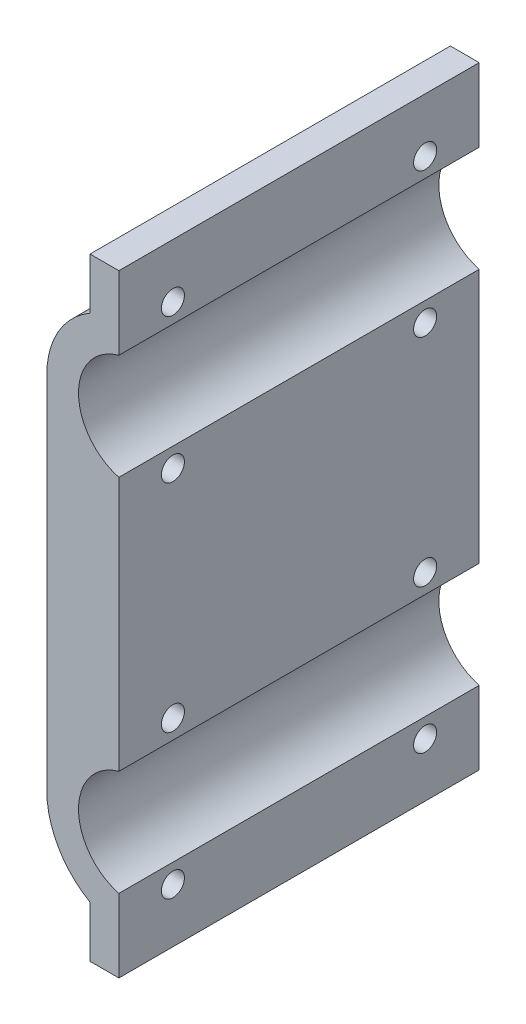
SolidWorks part; units mm, degrees
ref_plane "Plano frontal" through (0, 0, 0) normal (0, 0, 1) x (1, 0, 0)
ref_plane "Plano superior" through (0, 0, 0) normal (0, 1, 0) x (1, 0, 0)
ref_plane "Plano direito" through (0, 0, 0) normal (1, 0, 0) x (0, 0, -1)
sketch "Esboço1" plane through (0, 0, 0) normal (0, 0, 1) x (1, 0, 0)
  line L0 (0, 17.6679) -> (0, -17.6679) construction
  line L1 (0, 17.6679) -> (0, -17.6679)
  line L2 (-10, 25) -> (-10, -25)
  line L3 (0, -32.3321) -> (0, -42.5)
  line L4 (0, -42.5) -> (-4, -42.5)
  line L5 (-4, -42.5) -> (-4, -35.3923)
  line L6 (0, 32.3321) -> (0, 42.5)
  line L7 (0, 42.5) -> (-4, 42.5)
  line L8 (-4, 42.5) -> (-4, 35.3923)
  arc A0 (0, 32.3321) -> (0, 17.6679) centre (2, 25) ccw
  arc A1 (0, -17.6679) -> (0, -32.3321) centre (2, -25) ccw
  arc A2 (-4, 35.3923) -> (-10, 25) centre (2, 25) ccw
  arc A3 (-10, -25) -> (-4, -35.3923) centre (2, -25) ccw
  point P0 (0, 42.5)
  point P1 (2.9032, -24.6696)
  point P5 (0, 0)
  point P12 (0, 25.2871)
  point P15 (0, 0)
  dimension "D1" = 15.2
  dimension "D2" = 12
  dimension "D3" = 50
  dimension "D4" = 85
  dimension "D5" = 4
  dimension "D6" = 2
extrude "Ressalto-extrusão1" add sketch "Esboço1" along normal blind 50
sketch "Esboço2" plane through (0, 0, 0) normal (1, 0, 0) x (0, 0, -1)
  line L0 (-50, 25) -> (0, 25) construction
  line L1 (-50, -25) -> (0, -25) construction
  line L2 (-50, -17.6679) -> (-50, -32.3321) construction
  line L3 (0, -32.3321) -> (0, -17.6679) construction
  line L4 (-25, 42.5) -> (-25, -42.5) construction
  line L5 (-50, 42.5) -> (0, 42.5) construction
  line L6 (-50, -42.5) -> (0, -42.5) construction
  circle A0 centre (-42.5, 35) radius 1.6
  circle A1 centre (-7.5, 35) radius 1.6
  circle A2 centre (-7.5, -35) radius 1.6
  circle A3 centre (-42.5, -35) radius 1.6
  circle A4 centre (-42.5, -15) radius 1.6
  circle A5 centre (-42.5, 15) radius 1.6
  circle A6 centre (-7.5, 15) radius 1.6
  circle A7 centre (-7.5, -15) radius 1.6
  dimension "D4" = 3.2
  dimension "D1" = 20
  dimension "D2" = 20
  dimension "D3" = 35
extrude "Corte-extrusão1" cut sketch "Esboço2" against normal through all
sketch "Esboço3" plane through (-10, 0, 0) normal (-1, 0, 0) x (0, 0, 1)
  line L0 (0, 25) -> (0, -25) construction
  line L1 (10.25, 36.5877) -> (7.5, 38.1754)
  line L2 (7.5, 38.1754) -> (4.75, 36.5877)
  line L3 (4.75, 36.5877) -> (4.75, 33.4123)
  line L4 (4.75, 33.4123) -> (7.5, 31.8246)
  line L5 (7.5, 31.8246) -> (10.25, 33.4123)
  line L6 (10.25, 33.4123) -> (10.25, 36.5877)
  line L7 (45.25, 36.5877) -> (42.5, 38.1754)
  line L8 (42.5, 38.1754) -> (39.75, 36.5877)
  line L9 (39.75, 36.5877) -> (39.75, 33.4123)
  line L10 (39.75, 33.4123) -> (42.5, 31.8246)
  line L11 (42.5, 31.8246) -> (45.25, 33.4123)
  line L12 (45.25, 33.4123) -> (45.25, 36.5877)
  line L13 (45.25, 16.5877) -> (42.5, 18.1754)
  line L14 (42.5, 18.1754) -> (39.75, 16.5877)
  line L15 (39.75, 16.5877) -> (39.75, 13.4123)
  line L16 (39.75, 13.4123) -> (42.5, 11.8246)
  line L17 (42.5, 11.8246) -> (45.25, 13.4123)
  line L18 (45.25, 13.4123) -> (45.25, 16.5877)
  line L19 (10.25, 16.5877) -> (7.5, 18.1754)
  line L20 (7.5, 18.1754) -> (4.75, 16.5877)
  line L21 (4.75, 16.5877) -> (4.75, 13.4123)
  line L22 (4.75, 13.4123) -> (7.5, 11.8246)
  line L23 (7.5, 11.8246) -> (10.25, 13.4123)
  line L24 (10.25, 13.4123) -> (10.25, 16.5877)
  line L25 (10.25, -13.4123) -> (7.5, -11.8246)
  line L26 (7.5, -11.8246) -> (4.75, -13.4123)
  line L27 (4.75, -13.4123) -> (4.75, -16.5877)
  line L28 (4.75, -16.5877) -> (7.5, -18.1754)
  line L29 (7.5, -18.1754) -> (10.25, -16.5877)
  line L30 (10.25, -16.5877) -> (10.25, -13.4123)
  line L31 (10.25, -33.4123) -> (7.5, -31.8246)
  line L32 (7.5, -31.8246) -> (4.75, -33.4123)
  line L33 (4.75, -33.4123) -> (4.75, -36.5877)
  line L34 (4.75, -36.5877) -> (7.5, -38.1754)
  line L35 (7.5, -38.1754) -> (10.25, -36.5877)
  line L36 (10.25, -36.5877) -> (10.25, -33.4123)
  line L37 (45.25, -33.4123) -> (42.5, -31.8246)
  line L38 (42.5, -31.8246) -> (39.75, -33.4123)
  line L39 (39.75, -33.4123) -> (39.75, -36.5877)
  line L40 (39.75, -36.5877) -> (42.5, -38.1754)
  line L41 (42.5, -38.1754) -> (45.25, -36.5877)
  line L42 (45.25, -36.5877) -> (45.25, -33.4123)
  line L43 (45.25, -13.4123) -> (42.5, -11.8246)
  line L44 (42.5, -11.8246) -> (39.75, -13.4123)
  line L45 (39.75, -13.4123) -> (39.75, -16.5877)
  line L46 (39.75, -16.5877) -> (42.5, -18.1754)
  line L47 (42.5, -18.1754) -> (45.25, -16.5877)
  line L48 (45.25, -16.5877) -> (45.25, -13.4123)
  circle A0 centre (7.5, 35) radius 2.75 construction
  circle A1 centre (42.5, 35) radius 2.75 construction
  circle A2 centre (42.5, 15) radius 2.75 construction
  circle A3 centre (7.5, 15) radius 2.75 construction
  circle A4 centre (7.5, -15) radius 2.75 construction
  circle A5 centre (7.5, -35) radius 2.75 construction
  circle A6 centre (42.5, -35) radius 2.75 construction
  circle A7 centre (42.5, -15) radius 2.75 construction
  dimension "D1" = 5.5
extrude "Corte-extrusão2" cut sketch "Esboço3" against normal offset from surface 4 draft 2
equation "\"D2@Esboço2\"=\"D1@Esboço2\""
